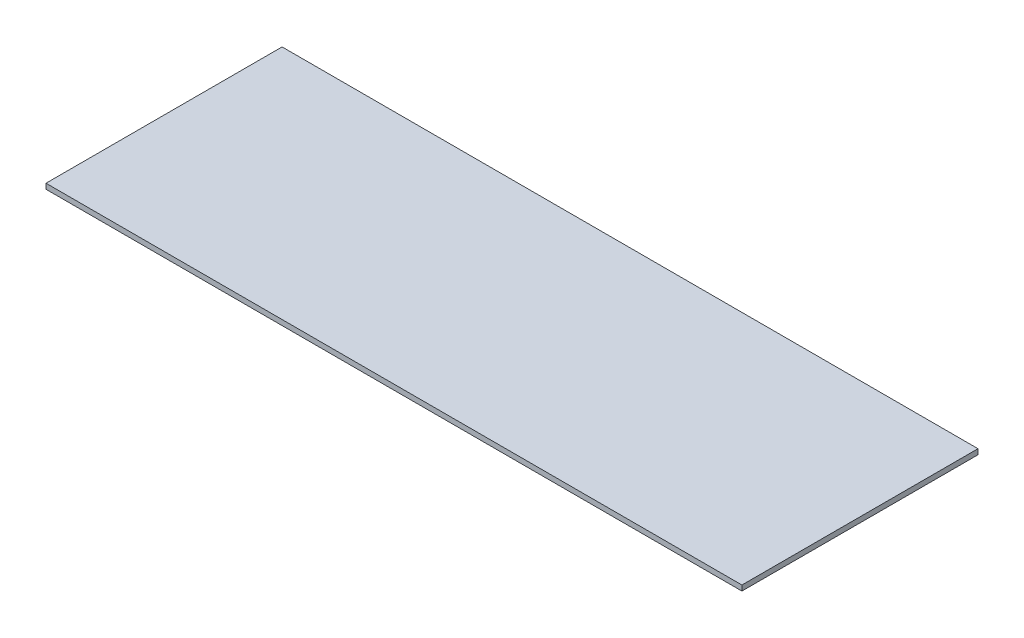
SolidWorks part; units mm, degrees
ref_plane "Front Plane" through (0, 0, 0) normal (0, 0, 1) x (1, 0, 0)
ref_plane "Top Plane" through (0, 0, 0) normal (0, 1, 0) x (1, 0, 0)
ref_plane "Right Plane" through (0, 0, 0) normal (1, 0, 0) x (0, 0, -1)
sketch "Sketch1" plane through (0, 0, 0) normal (0, 1, 0) x (1, 0, 0)
  line L1 (-265.0522, 19.5222) -> (129.9478, 19.5222)
  line L2 (-265.0522, 19.5222) -> (-265.0522, -114.4778)
  line L3 (-265.0522, -114.4778) -> (129.9478, -114.4778)
  line L4 (129.9478, 19.5222) -> (129.9478, -114.4778)
  dimension "D1" = 395
  dimension "D2" = 134
extrude "Boss-Extrude1" add sketch "Sketch1" along normal blind 3
